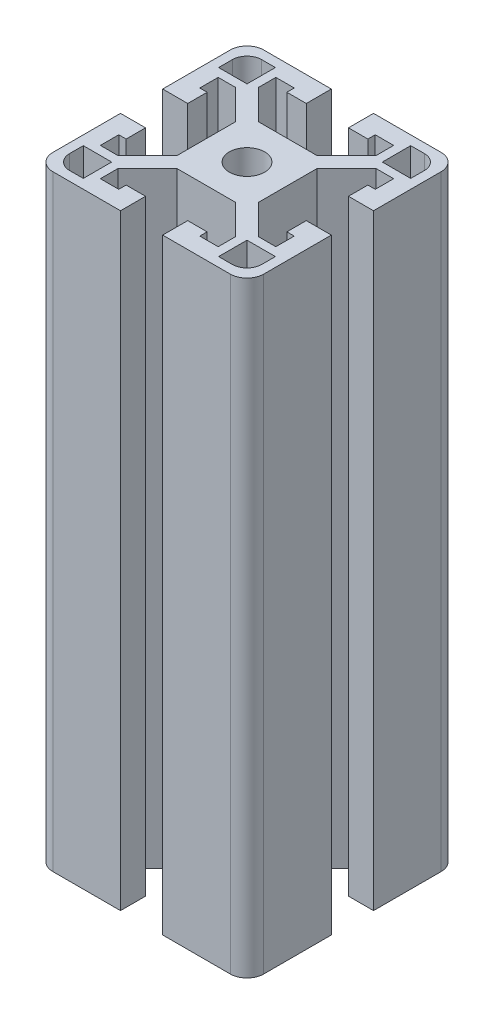
SolidWorks part; units mm, degrees
material "6063-T6"
ref_plane "Front Plane" through (0, 0, 0) normal (0, 0, 1) x (1, 0, 0)
ref_plane "Top Plane" through (0, 0, 0) normal (0, 1, 0) x (1, 0, 0)
ref_plane "Right Plane" through (0, 0, 0) normal (1, 0, 0) x (0, 0, -1)
sketch "Sketch1" plane through (0, 0, 0) normal (0, 0, 1) x (1, 0, 0)
  line L0 (0, 0) -> (0, 115)
  dimension "D1" = 115
other "40 series TS40-40LM-650033(2)"
ref_plane "Plane2" through (0, 0, 0) normal (0, 1, 0) x (-1, 0, 0)
sketch "Sketch2" plane through (0, 0, 0) normal (0, 1, 0) x (-1, 0, 0)
  line L2 (-7.7064, 0) -> (-7.7064, 5.5511)
  line L3 (-7.7064, 5.5511) -> (-13.3313, 11.176)
  line L4 (-16.6472, 11.176) -> (-16.6472, 7.6835)
  line L5 (5.5511, 7.7064) -> (11.176, 13.3313)
  line L6 (-20, 4.0005) -> (-20, 16.825)
  line L7 (0, 7.7064) -> (-5.5511, 7.7064)
  line L8 (-5.5511, 7.7064) -> (-11.176, 13.3313)
  line L9 (-11.176, 16.6472) -> (-7.6835, 16.6472)
  line L10 (4.0005, 20) -> (16.825, 20)
  line L11 (-4.0005, 20) -> (-16.825, 20)
  line L12 (20, 4.0005) -> (20, 16.825)
  line L13 (7.7064, 5.5511) -> (13.3313, 11.176)
  line L14 (18.222, 12.8372) -> (18.222, 15.428)
  line L15 (12.8372, 18.222) -> (15.428, 18.222)
  line L16 (7.7064, 0) -> (7.7064, 5.5511)
  line L17 (7.7064, 0) -> (7.7064, -5.5511)
  line L18 (7.6835, 16.6472) -> (7.6835, 15.2502)
  line L19 (4.0005, 15.2502) -> (7.6835, 15.2502)
  line L20 (11.176, -13.3313) -> (11.176, -16.6472)
  line L21 (13.3313, -11.176) -> (16.6472, -11.176)
  line L22 (20, -4.0005) -> (20, -16.825)
  line L23 (-4.0005, -20) -> (-16.825, -20)
  line L24 (4.0005, -20) -> (16.825, -20)
  line L25 (12.8372, -12.8372) -> (18.222, -12.8372)
  line L26 (-18.222, -12.8372) -> (-18.222, -15.428)
  line L27 (-12.8372, -18.222) -> (-15.428, -18.222)
  line L28 (-20, -4.0005) -> (-20, -16.825)
  line L29 (-12.8372, -12.8372) -> (-12.8372, -18.222)
  line L30 (-12.8372, -12.8372) -> (-18.222, -12.8372)
  line L31 (12.8372, -12.8372) -> (12.8372, -18.222)
  line L32 (-7.7064, 0) -> (-7.7064, -5.5511)
  line L33 (0, 7.7064) -> (5.5511, 7.7064)
  line L34 (-4.0005, 20) -> (-4.0005, 15.2502)
  line L35 (4.0005, 20) -> (4.0005, 15.2502)
  line L36 (-15.2502, 4.0005) -> (-20, 4.0005)
  line L37 (15.2502, 4.0005) -> (15.2502, 7.6835)
  line L38 (16.6472, 7.6835) -> (15.2502, 7.6835)
  line L39 (15.2502, 4.0005) -> (20, 4.0005)
  line L40 (11.176, 16.6472) -> (7.6835, 16.6472)
  line L41 (16.6472, 11.176) -> (16.6472, 7.6835)
  line L42 (-11.176, 13.3313) -> (-11.176, 16.6472)
  line L43 (-13.3313, 11.176) -> (-16.6472, 11.176)
  line L44 (12.8372, 12.8372) -> (12.8372, 18.222)
  line L45 (-12.8372, 12.8372) -> (-18.222, 12.8372)
  line L46 (-12.8372, 12.8372) -> (-12.8372, 18.222)
  line L47 (-12.8372, 18.222) -> (-15.428, 18.222)
  line L48 (-18.222, 12.8372) -> (-18.222, 15.428)
  line L49 (12.8372, 12.8372) -> (18.222, 12.8372)
  line L50 (13.3313, 11.176) -> (16.6472, 11.176)
  line L51 (11.176, 13.3313) -> (11.176, 16.6472)
  line L52 (-11.176, -16.6472) -> (-7.6835, -16.6472)
  line L53 (11.176, -16.6472) -> (7.6835, -16.6472)
  line L54 (-13.3313, -11.176) -> (-16.6472, -11.176)
  line L55 (-11.176, -13.3313) -> (-11.176, -16.6472)
  line L56 (0, -7.7064) -> (5.5511, -7.7064)
  line L57 (12.8372, -18.222) -> (15.428, -18.222)
  line L58 (18.222, -12.8372) -> (18.222, -15.428)
  line L59 (7.7064, -5.5511) -> (13.3313, -11.176)
  line L60 (16.6472, -11.176) -> (16.6472, -7.6835)
  line L61 (-5.5511, -7.7064) -> (-11.176, -13.3313)
  line L62 (0, -7.7064) -> (-5.5511, -7.7064)
  line L63 (5.5511, -7.7064) -> (11.176, -13.3313)
  line L64 (15.2502, -4.0005) -> (20, -4.0005)
  line L65 (-7.7064, -5.5511) -> (-13.3313, -11.176)
  line L66 (16.6472, -7.6835) -> (15.2502, -7.6835)
  line L67 (15.2502, -4.0005) -> (15.2502, -7.6835)
  line L68 (4.0005, -20) -> (4.0005, -15.2502)
  line L69 (-4.0005, 15.2502) -> (-7.6835, 15.2502)
  line L70 (-7.6835, 16.6472) -> (-7.6835, 15.2502)
  line L71 (4.0005, -15.2502) -> (7.6835, -15.2502)
  line L72 (7.6835, -16.6472) -> (7.6835, -15.2502)
  line L73 (-16.6472, 7.6835) -> (-15.2502, 7.6835)
  line L74 (-15.2502, 4.0005) -> (-15.2502, 7.6835)
  line L75 (-7.6835, -16.6472) -> (-7.6835, -15.2502)
  line L76 (-4.0005, -15.2502) -> (-7.6835, -15.2502)
  line L77 (-4.0005, -20) -> (-4.0005, -15.2502)
  line L78 (-15.2502, -4.0005) -> (-15.2502, -7.6835)
  line L79 (-16.6472, -7.6835) -> (-15.2502, -7.6835)
  line L80 (-15.2502, -4.0005) -> (-20, -4.0005)
  line L81 (-16.6472, -11.176) -> (-16.6472, -7.6835)
  arc A0 (-16.825, 20) -> (-20, 16.825) centre (-16.825, 16.825) ccw
  arc A1 (-15.428, 18.222) -> (-18.222, 15.428) centre (-15.428, 15.428) ccw
  arc A2 (15.428, 18.222) -> (18.222, 15.428) centre (15.428, 15.428) cw
  arc A3 (-15.428, -18.222) -> (-18.222, -15.428) centre (-15.428, -15.428) cw
  arc A4 (15.428, -18.222) -> (18.222, -15.428) centre (15.428, -15.428) ccw
  arc A5 (16.825, 20) -> (20, 16.825) centre (16.825, 16.825) cw
  arc A6 (16.825, -20) -> (20, -16.825) centre (16.825, -16.825) ccw
  arc A7 (-16.825, -20) -> (-20, -16.825) centre (-16.825, -16.825) cw
  circle A8 centre (0, 0) radius 3.35
  point P1 (-20, 20)
  point P2 (0, 20)
  point P100 (20, 20)
  point P101 (20, 0)
  point P102 (20, -20)
  point P103 (0, -20)
  point P104 (-20, -20)
  point P105 (-20, 0)
  point P106 (0, 0)
  dimension "D1" = 6.7
hole_wizard "M8x1.25 Tapped Hole3" positions "Sketch3" profile "Sketch4" tap size "M8x1.25" standard "ANSI Metric"
sketch "Sketch3" plane through (0, 0, 0) normal (0, -1, 0) x (-1, 0, 0)
  point P0 (0, 0)
sketch "Sketch4" plane through (0, 0, 0) normal (1, 0, 0) x (0, 0, -1)
  line L0 (0, 0) -> (0, 27.0429)
  line L1 (0, 27.0429) -> (3.4, 25)
  line L2 (3.4, 25) -> (3.4, 0)
  line L5 (3.4, 0) -> (0, 0)
  line L10 (0, 27.0429) -> (-3.4, 25) construction
  line L11 (0, -6.35) -> (0, 107.95) construction
  dimension "Tap Drill Dia." = 6.8
  dimension "Tap Drill Depth" = 25
  dimension "Drill Angle" = 118
cosmetic thread "Hole Thread1"
